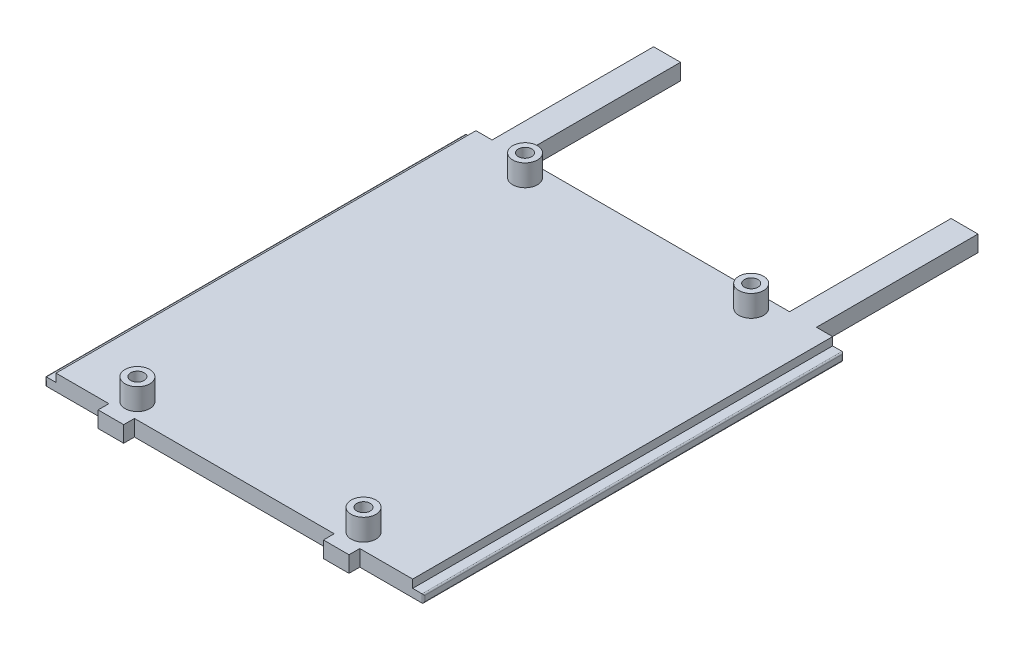
SolidWorks part; units mm, degrees
ref_plane "Front Plane" through (0, 0, 0) normal (0, 0, 1) x (1, 0, 0)
ref_plane "Top Plane" through (0, 0, 0) normal (0, 1, 0) x (1, 0, 0)
ref_plane "Right Plane" through (0, 0, 0) normal (1, 0, 0) x (0, 0, -1)
sketch "Sketch1" plane through (0, 0, 0) normal (0, 1, 0) x (1, 0, 0)
  line L0 (-33.125, 0) -> (33.125, 0) construction
  line L1 (-33.125, 39) -> (33.125, 39)
  line L2 (-33.125, 39) -> (-33.125, -39)
  line L3 (-33.125, -39) -> (33.125, -39)
  line L4 (33.125, 39) -> (33.125, -39)
  line L5 (-33.125, 39) -> (33.125, -39) construction
  line L6 (-33.125, -39) -> (33.125, 39) construction
  line L7 (0, 39) -> (0, -39) construction
  circle A0 centre (-21, 36) radius 1.25
  circle A1 centre (21, 36) radius 1.25
  circle A2 centre (21, -36) radius 1.25
  circle A3 centre (-21, -36) radius 1.25
  point P0 (0, 0)
  dimension "D3" = 21
  dimension "D1" = 66.25
  dimension "D2" = 78
  dimension "D4" = 36
extrude "Boss-Extrude1" add sketch "Sketch1" along normal blind 3
sketch "Sketch2" plane through (0, 0, 0) normal (0, -1, 0) x (1, 0, 0)
  line L0 (-33.125, 39) -> (33.125, 39) construction
  line L1 (-35.125, -39) -> (-25.3776, -39)
  line L2 (-35.125, -39) -> (-35.125, 39)
  line L3 (-35.125, 39) -> (-25.3776, 39)
  line L4 (35.125, -39) -> (35.125, 39)
  line L5 (-35.125, -39) -> (35.125, 39) construction
  line L6 (-35.125, 39) -> (35.125, -39) construction
  line L7 (-25.3776, -39) -> (-25.3776, 39)
  line L8 (24.7368, -39) -> (24.7368, 39)
  line L9 (24.7368, -39) -> (35.125, -39)
  line L10 (24.7368, 39) -> (35.125, 39)
  point P0 (0, 0)
  dimension "D1" = 70.25
extrude "Boss-Extrude2" add sketch "Sketch2" against normal blind 1.5
fillet "Fillet2" radius 0.25 4 edges at (-35.125, 0.75, 39) (-35.125, 0.75, -39) (-35.125, 1.5, 0) (-35.125, 0, 0)
fillet "Fillet3" radius 0.25 4 edges at (35.125, 0.75, -39) (35.125, 1.5, 0) (35.125, 0, 0) (35.125, 0.75, 39)
sketch "Sketch3" plane through (0, 3, 0) normal (0, 1, 0) x (1, 0, 0)
  line L0 (0, 39) -> (0, -39) construction
  line L1 (33.125, 39) -> (-33.125, 39) construction
  line L2 (-33.125, -39) -> (33.125, -39) construction
  line L3 (-33.125, 0) -> (33.125, 0) construction
  line L4 (-33.125, 39) -> (-33.125, -39) construction
  line L5 (33.125, -39) -> (33.125, 39) construction
  circle A0 centre (-21, 36) radius 2.3
  circle A4 centre (-21, 36) radius 1.25
  circle A5 centre (21, 36) radius 1.25
  circle A6 centre (21, 36) radius 2.3
  circle A7 centre (21, -36) radius 2.3
  circle A8 centre (21, -36) radius 1.25
  circle A9 centre (-21, -36) radius 1.25
  circle A10 centre (-21, -36) radius 2.3
  dimension "D1" = 42
extrude "Boss-Extrude3" add sketch "Sketch3" along normal blind 4
sketch "Sketch4" plane through (0, 0, 39) normal (0, 0, 1) x (1, 0, 0)
  line L0 (-34.875, 0) -> (34.875, 0) construction
  line L1 (-23.3, 3) -> (-18.55, 3)
  line L2 (-23.3, 3) -> (-23.3, 0)
  line L3 (-23.3, 0) -> (-18.55, 0)
  line L4 (-18.55, 3) -> (-18.55, 0)
  line L5 (0, 0) -> (0, 7.2444) construction
  line L6 (18.55, 3) -> (18.55, 0)
  line L7 (23.3, 0) -> (18.55, 0)
  line L8 (23.3, 3) -> (23.3, 0)
  line L9 (23.3, 3) -> (18.55, 3)
extrude "Boss-Extrude4" add sketch "Sketch4" along normal blind 2
sketch "Sketch5" plane through (0, 0, -39) normal (0, 0, -1) x (-1, 0, 0)
  line L0 (-33.125, 3) -> (33.125, 3) construction
  line L1 (-30.125, 3) -> (-25.125, 3)
  line L2 (-30.125, 3) -> (-30.125, 0)
  line L3 (-30.125, 0) -> (-25.125, 0)
  line L4 (-25.125, 3) -> (-25.125, 0)
  line L5 (-34.875, 0) -> (34.875, 0) construction
  line L6 (-35.125, 0.25) -> (-35.125, 1.25) construction
  line L7 (0, 0) -> (0, 7.0524) construction
  line L8 (25.125, 3) -> (25.125, 0)
  line L9 (30.125, 0) -> (25.125, 0)
  line L10 (30.125, 3) -> (30.125, 0)
  line L11 (30.125, 3) -> (25.125, 3)
  dimension "D1" = 5
extrude "Boss-Extrude5" add sketch "Sketch5" along normal blind 30
